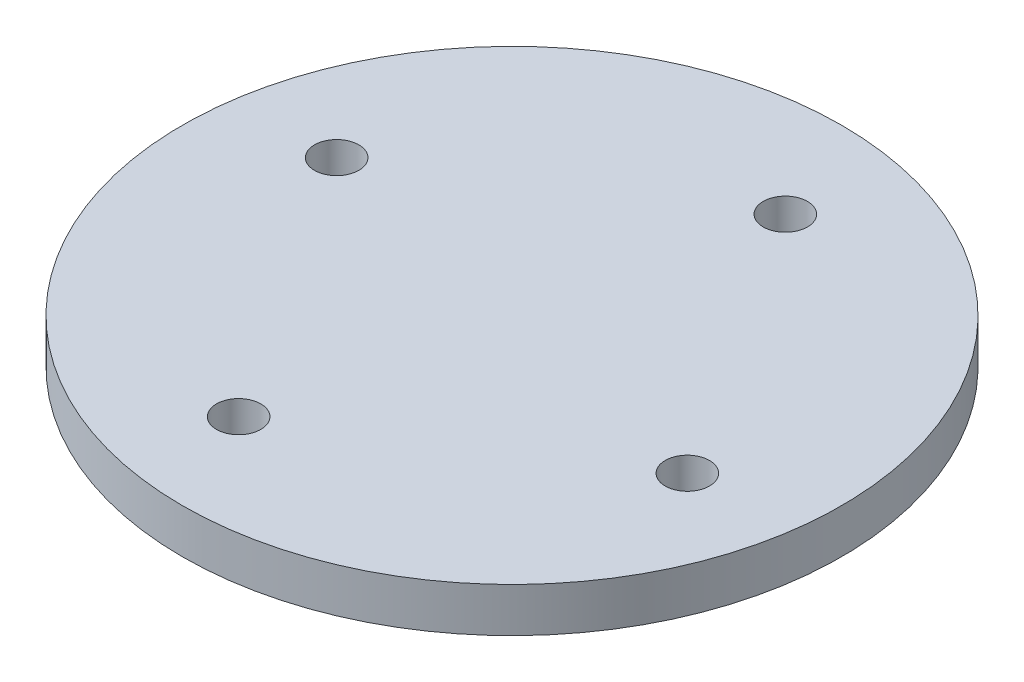
SolidWorks part; units mm, degrees
ref_plane "Front Plane" through (0, 0, 0) normal (0, 0, 1) x (1, 0, 0)
ref_plane "Top Plane" through (0, 0, 0) normal (0, 1, 0) x (1, 0, 0)
ref_plane "Right Plane" through (0, 0, 0) normal (1, 0, 0) x (0, 0, -1)
sketch "Sketch1" plane through (0, 0, 0) normal (0, 1, 0) x (1, 0, 0)
  circle A0 centre (0, 0) radius 14.875
  circle A1 centre (0, 0) radius 10.365
  circle A2 centre (2.2116, 10.1263) radius 1
  circle A3 centre (10.1263, -2.2116) radius 1
  circle A4 centre (-2.2116, -10.1263) radius 1
  circle A5 centre (-10.1263, 2.2116) radius 1
  point P15 (0, 0)
  dimension "D1" = 20.73
  dimension "30" = 29.75
  dimension "D2" = 2
  dimension "D3" = 4
extrude "Boss-Extrude1" add sketch "Sketch1" along normal blind 2 contours A0 A5 A1 A2 A3 A4 | A5 A1 A4 A3 A2
